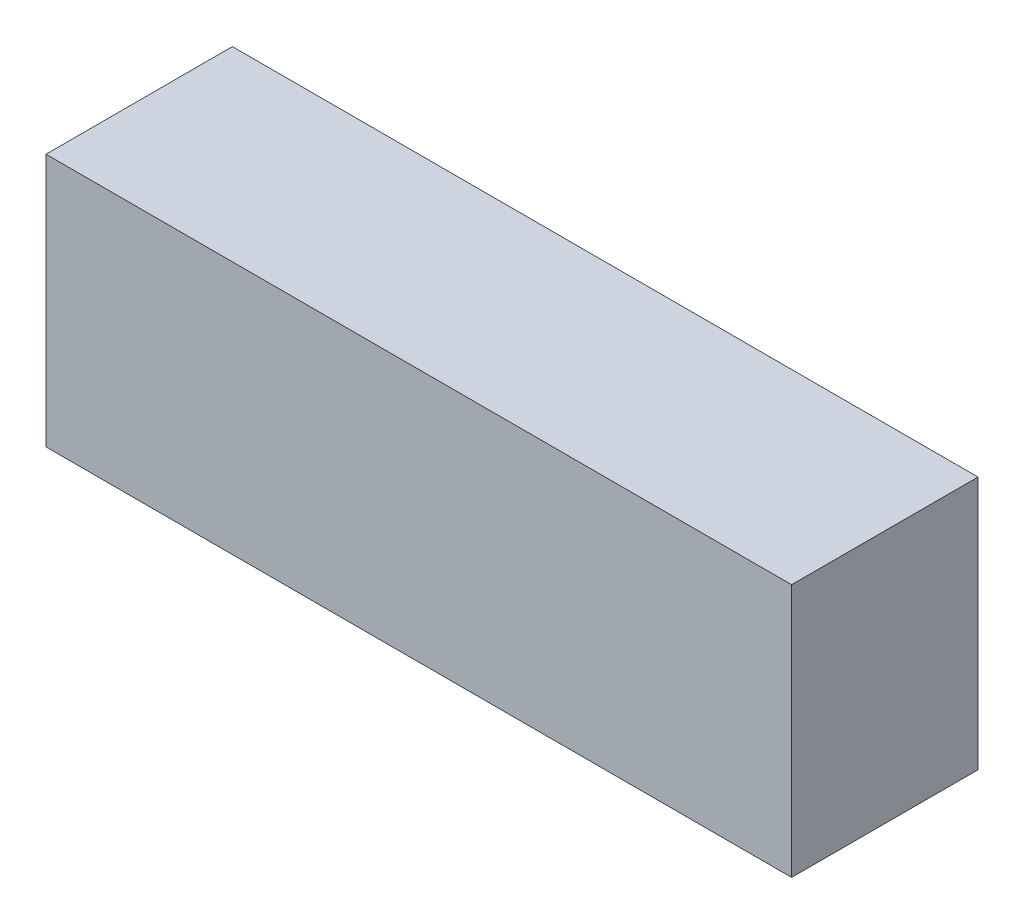
SolidWorks part; units mm, degrees
ref_plane "Ebene vorne" through (0, 0, 0) normal (0, 0, 1) x (1, 0, 0)
ref_plane "Ebene oben" through (0, 0, 0) normal (0, 1, 0) x (1, 0, 0)
ref_plane "Ebene rechts" through (0, 0, 0) normal (1, 0, 0) x (0, 0, -1)
sketch "Skizze1" plane through (0, 0, 0) normal (0, 0, 1) x (1, 0, 0)
  line L1 (0, 0) -> (100, 0)
  line L2 (0, 0) -> (0, 34)
  line L3 (0, 34) -> (100, 34)
  line L4 (100, 0) -> (100, 34)
  dimension "D1" = 100
  dimension "D2" = 34
extrude "Aufsatz-Linear austragen1" add sketch "Skizze1" along normal blind 25
